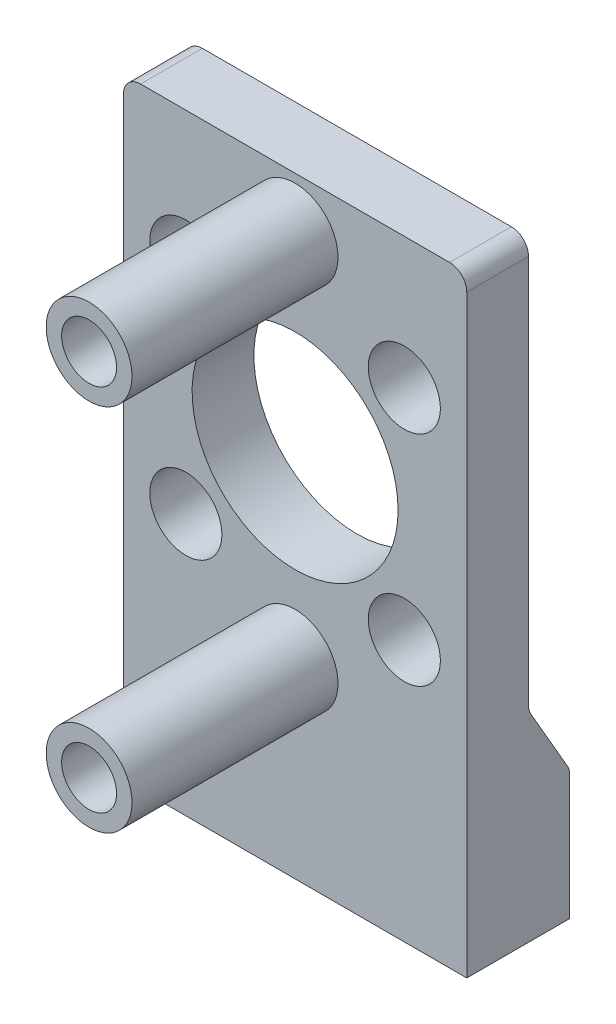
SolidWorks part; units mm, degrees
ref_plane "前视基准面" through (0, 0, 0) normal (0, 0, 1) x (1, 0, 0)
ref_plane "上视基准面" through (0, 0, 0) normal (0, 1, 0) x (1, 0, 0)
ref_plane "右视基准面" through (0, 0, 0) normal (1, 0, 0) x (0, 0, -1)
sketch "草图1" plane through (0, 0, 0) normal (0, 0, 1) x (1, 0, 0)
  line L0 (-5, -9.7827) -> (-5, -10.0827)
  line L2 (5, -4.6124) -> (5, 7.7173)
  line L3 (5, 7.7173) -> (-5, 7.7173)
  line L4 (-5, -9.7827) -> (-5, 7.7173)
  line L7 (-5, -10.0827) -> (5, -10.0827)
  line L8 (5, -10.0827) -> (5, -4.6124)
  point P0 (0, 0)
  dimension "D1" = 17.8
  dimension "D2" = 5
  dimension "D3" = 10
extrude "凸台-拉伸1" add sketch "草图1" along normal blind 3
sketch "草图2" plane through (0, -10.0827, 0) normal (0, -1, 0) x (-1, 0, 0)
  line L0 (0, 0) -> (0, -50000) construction
  line L1 (-55, 0) -> (55, 0) construction
  circle A0 centre (3, -1.5) radius 0.8
  circle A1 centre (-3, -1.5) radius 0.8
  dimension "D1" = 3
  dimension "D2" = 1.5
extrude "切除-拉伸1" cut sketch "草图2" against normal blind 3.5 contours A1 | A0
sketch "草图6" plane through (0, 0, 0) normal (0, 0, -1) x (-1, 0, 0)
  line L0 (-5, 7.7173) -> (5, 7.7173) construction
  circle A0 centre (0, 0.7173) radius 3
  circle A1 centre (0, 0.7173) radius 4.5 construction
  circle A2 centre (-3.182, 3.8993) radius 1.05
  circle A3 centre (3.182, 3.8993) radius 1.05
  circle A4 centre (3.182, -2.4647) radius 1.05
  circle A5 centre (-3.182, -2.4647) radius 1.05
  dimension "D1" = 7
  dimension "D2" = 4
extrude "切除-拉伸2" cut sketch "草图6" against normal blind 5
sketch "草图7" plane through (0, 0, 0) normal (0, 0, -1) x (-1, 0, 0)
  line L0 (0, 0) -> (0, 2.3652) construction
  line L2 (5, -10.0827) -> (-5, -10.0827) construction
  circle A0 centre (0, 6.2173) radius 0.8
  circle A2 centre (0, -4.5327) radius 0.8
  circle A3 centre (0, 0.7173) radius 3 construction
  dimension "D1" = 5.5
  dimension "D3" = 3
  dimension "D2" = 5.55
  dimension "D4" = 10.75
  dimension "D5" = 5.25
fillet "圆角1" radius 0.5 2 edges at (-5, 7.7173, 1.5) (5, 7.7173, 1.5)
sketch "草图12" plane through (5, 0, 0) normal (1, 0, 0) x (0, 0, -1)
  line L1 (-1.2, 7.7173) -> (-1.2, -4.2438)
  line L2 (-1.2, -4.2438) -> (0, -6.3223)
  line L3 (0, -6.3223) -> (0, 7.7173)
  line L4 (0, 7.7173) -> (-1.2, 7.7173)
  line L5 (-3, 7.7173) -> (0, 7.7173) construction
  dimension "D1" = 30
  dimension "D2" = 1.2
extrude "切除-拉伸4" cut sketch "草图12" against normal through all
fillet "圆角2" radius 0.5 2 edges at (0, -6.3223, 0) (0, -4.2438, 1.2)
sketch "草图13" plane through (0, 0, 3) normal (0, 0, 1) x (1, 0, 0)
  circle A0 centre (0, 6.2173) radius 0.8
  circle A1 centre (0, -4.5327) radius 0.8
  circle A2 centre (0, 6.2173) radius 1.25
  circle A3 centre (0, -4.5327) radius 1.25
extrude "凸台-拉伸2" add sketch "草图13" along normal blind 6
